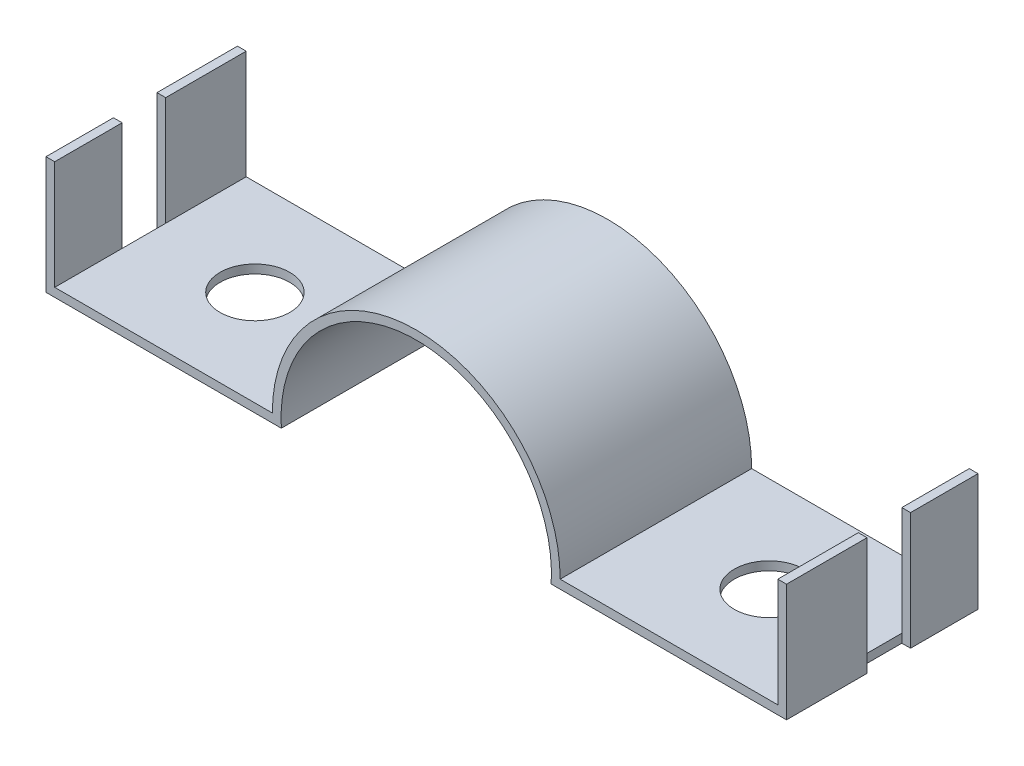
SolidWorks part; units mm, degrees
material "Brass"
ref_plane "Front Plane" through (0, 0, 0) normal (0, 0, 1) x (1, 0, 0)
ref_plane "Top Plane" through (0, 0, 0) normal (0, 1, 0) x (1, 0, 0)
ref_plane "Right Plane" through (0, 0, 0) normal (1, 0, 0) x (0, 0, -1)
sketch "Sketch1" plane through (0, 0, 0) normal (0, 0, 1) x (1, 0, 0)
  line L1 (8.3984, 0) -> (21.0984, 0)
  line L2 (-8.3984, 0) -> (-21.0984, 0)
  line L3 (21.0984, 0) -> (21.0984, 6.35)
  line L4 (-21.0984, 0) -> (-21.0984, 6.35)
  line L5 (-21.6064, -0.508) -> (-21.6064, 6.35)
  line L6 (-7.874, -0.508) -> (-21.6064, -0.508)
  line L7 (7.874, -0.508) -> (21.6064, -0.508)
  line L8 (21.6064, -0.508) -> (21.6064, 6.35)
  line L9 (-21.0984, 6.35) -> (-21.6064, 6.35)
  line L10 (21.0984, 6.35) -> (21.6064, 6.35)
  arc A0 (-8.3984, 0) -> (8.3984, 0) centre (0, 0) cw
  arc A1 (-7.8904, 0) -> (7.8904, 0) centre (0, 0) cw
  arc A2 (-7.874, -0.508) -> (7.874, -0.508) centre (0, 0) cw
  dimension "D1" = 7.874
  dimension "D3" = 12.7
  dimension "D4" = 12.7
  dimension "D5" = 6.35
  dimension "D6" = 6.35
  dimension "D2" = 0.508
  dimension "D7" = 0.508
extrude "Boss-Extrude1" add sketch "Sketch1" along normal blind 11.176 contours A0 L1 L3 L10 L8 L7 A2 L6 L5 L9 L4 L2
sketch "Sketch2" plane through (0, 0, 0) normal (0, 1, 0) x (1, 0, 0)
  line L2 (-21.0984, -11.176) -> (-21.0984, 0) construction
  line L5 (-8.3984, -11.176) -> (-21.0984, -11.176) construction
  line L8 (8.3984, 0) -> (21.0984, 0) construction
  line L9 (21.0984, -11.176) -> (21.0984, 0) construction
  circle A0 centre (15.0024, -5.588) radius 2.032
  circle A1 centre (-15.0024, -5.588) radius 2.032
  dimension "D1" = 5.588
  dimension "D5" = 4.064
  dimension "D2" = 6.096
  dimension "D3" = 6.096
  dimension "D4" = 5.588
extrude "Cut-Extrude1" cut sketch "Sketch2" against normal through all contours A1 | A0
sketch "Sketch4" plane through (21.6064, 0, 0) normal (1, 0, 0) x (0, 0, -1)
  line L0 (-11.176, -0.508) -> (0, -0.508) construction
  line L1 (-6.477, -0.508) -> (-3.937, -0.508)
  line L2 (-6.477, -0.508) -> (-6.477, 6.35)
  line L3 (-6.477, 6.35) -> (-3.937, 6.35)
  line L4 (-3.937, -0.508) -> (-3.937, 6.35)
  line L5 (-11.176, 6.35) -> (0, 6.35) construction
  point P8 (-5.207, -0.508)
  dimension "D1" = 2.54
  dimension "D2" = 5.207
extrude "Cut-Extrude2" cut sketch "Sketch4" against normal up to surface (0.508 mm away) up to face at (21.0984, 3.175, 5.588)
sketch "Sketch5" plane through (-21.6064, 0, 0) normal (-1, 0, 0) x (0, 0, 1)
  line L0 (11.176, -0.508) -> (0, -0.508) construction
  line L1 (4.699, -0.508) -> (7.239, -0.508)
  line L2 (4.699, -0.508) -> (4.699, 6.35)
  line L3 (4.699, 6.35) -> (7.239, 6.35)
  line L4 (7.239, -0.508) -> (7.239, 6.35)
  line L5 (11.176, 6.35) -> (0, 6.35) construction
  point P8 (5.969, -0.508)
  dimension "D1" = 2.54
  dimension "D2" = 5.207
extrude "Cut-Extrude3" cut sketch "Sketch5" against normal up to surface (0.508 mm away) up to face at (-21.0984, 3.175, 5.588)
